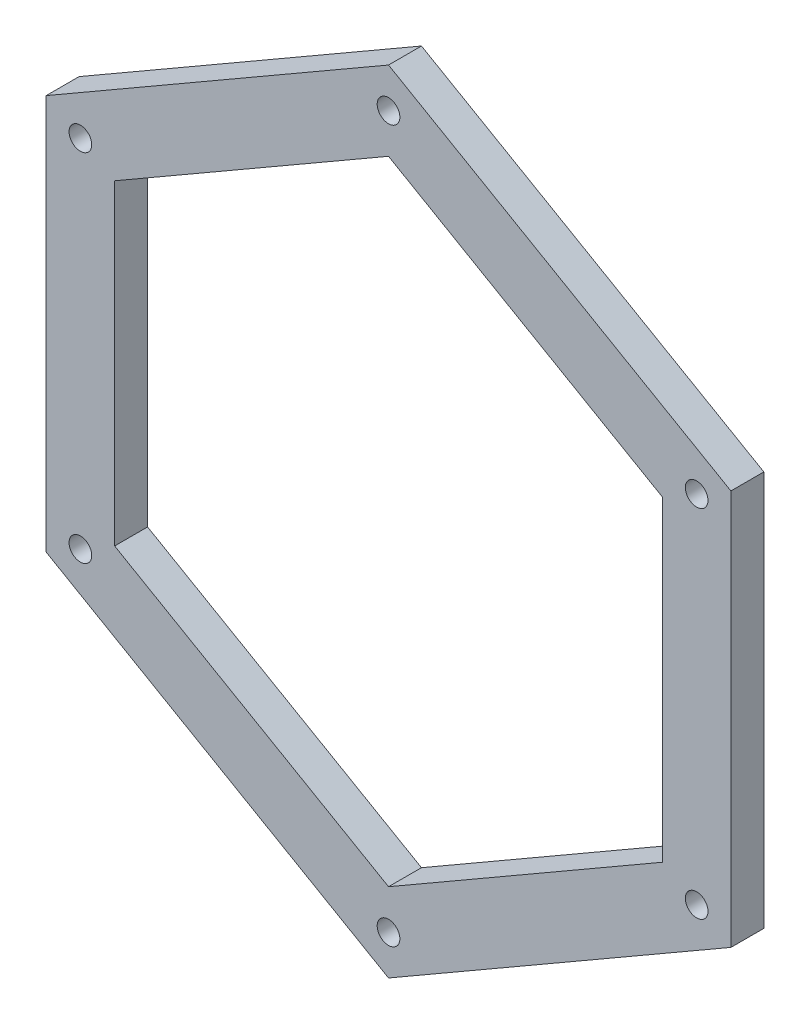
SolidWorks part; units mm, degrees
ref_plane "Front Plane" through (0, 0, 0) normal (0, 0, 1) x (1, 0, 0)
ref_plane "Top Plane" through (0, 0, 0) normal (0, 1, 0) x (1, 0, 0)
ref_plane "Right Plane" through (0, 0, 0) normal (1, 0, 0) x (0, 0, -1)
sketch "Sketch1" plane through (0, 0, 0) normal (0, 0, 1) x (1, 0, 0)
  line L0 (-32.9956, 19.05) -> (-26.3965, 15.24) construction
  line L1 (32.9956, 19.05) -> (0, 38.1)
  line L2 (0, 38.1) -> (-32.9956, 19.05)
  line L3 (-32.9956, 19.05) -> (-32.9956, -19.05)
  line L4 (-32.9956, -19.05) -> (0, -38.1)
  line L5 (0, -38.1) -> (32.9956, -19.05)
  line L6 (32.9956, -19.05) -> (32.9956, 19.05)
  line L7 (26.3965, 15.24) -> (0, 30.48)
  line L8 (0, 30.48) -> (-26.3965, 15.24)
  line L9 (-26.3965, 15.24) -> (-26.3965, -15.24)
  line L10 (-26.3965, -15.24) -> (0, -30.48)
  line L11 (0, -30.48) -> (26.3965, -15.24)
  line L12 (26.3965, -15.24) -> (26.3965, 15.24)
  circle A0 centre (0, 0) radius 32.9956 construction
  circle A1 centre (0, 0) radius 26.3965 construction
  circle A2 centre (-29.696, 17.145) radius 1.0922
  circle A3 centre (0, 34.29) radius 1.0922
  circle A4 centre (0, 0) radius 26.3965 construction
  circle A5 centre (29.696, 17.145) radius 1.0922
  circle A6 centre (0, 0) radius 26.3965 construction
  circle A7 centre (29.696, -17.145) radius 1.0922
  circle A8 centre (0, 0) radius 26.3965 construction
  circle A9 centre (0, -34.29) radius 1.0922
  circle A10 centre (0, 0) radius 26.3965 construction
  circle A11 centre (-29.696, -17.145) radius 1.0922
  circle A12 centre (0, 0) radius 26.3965 construction
  point P36 (0, 0)
  dimension "D3" = 2.1844
  dimension "D4" = 6
  dimension "D1" = 38.1
  dimension "D2" = 30.48
  dimension "D5" = 3.81
extrude "Boss-Extrude1" add sketch "Sketch1" along normal blind 3.175
